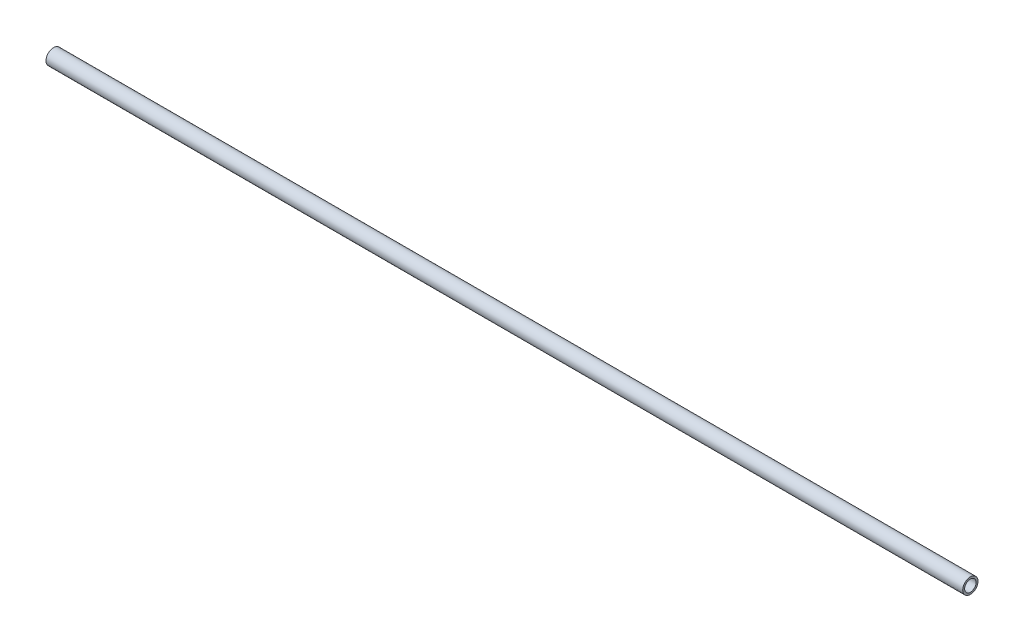
SolidWorks part; units mm, degrees
ref_plane "Front Plane" through (0, 0, 0) normal (0, 0, 1) x (1, 0, 0)
ref_plane "Top Plane" through (0, 0, 0) normal (0, 1, 0) x (1, 0, 0)
ref_plane "Right Plane" through (0, 0, 0) normal (1, 0, 0) x (0, 0, -1)
sketch "Sketch2" plane through (0, 0, 0) normal (1, 0, 0) x (0, 0, -1)
  circle A0 centre (0, 0) radius 9.525
  circle A1 centre (0, 0) radius 12.7
  dimension "D1" = 19.05
  dimension "D2" = 3.175
extrude "Boss-Extrude1" add sketch "Sketch2" along normal blind 1524
